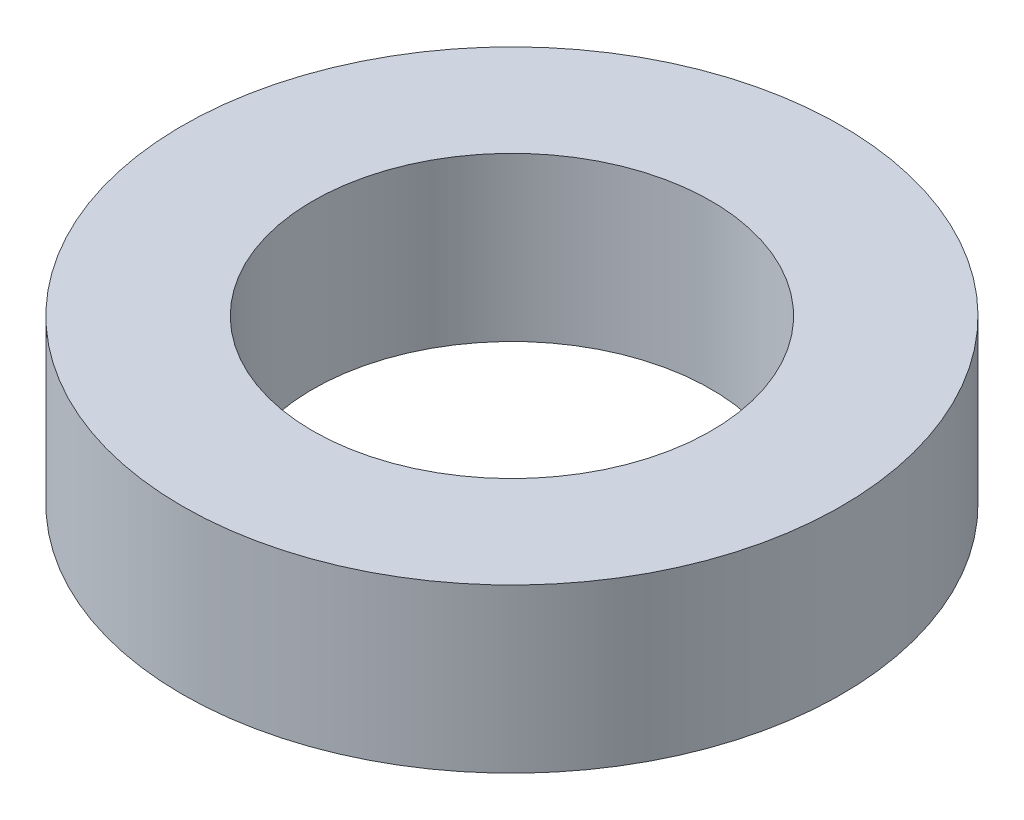
SolidWorks part; units mm, degrees
ref_plane "Спереди" through (0, 0, 0) normal (0, 0, 1) x (1, 0, 0)
ref_plane "Сверху" through (0, 0, 0) normal (0, 1, 0) x (1, 0, 0)
ref_plane "Справа" through (0, 0, 0) normal (1, 0, 0) x (0, 0, -1)
sketch "Эскиз1" plane through (0, 0, 0) normal (0, 1, 0) x (1, 0, 0)
  circle A0 centre (0, 0) radius 18.2
  circle A1 centre (0, 0) radius 11
extrude "Вытянуть1" add sketch "Эскиз1" along normal blind 9
